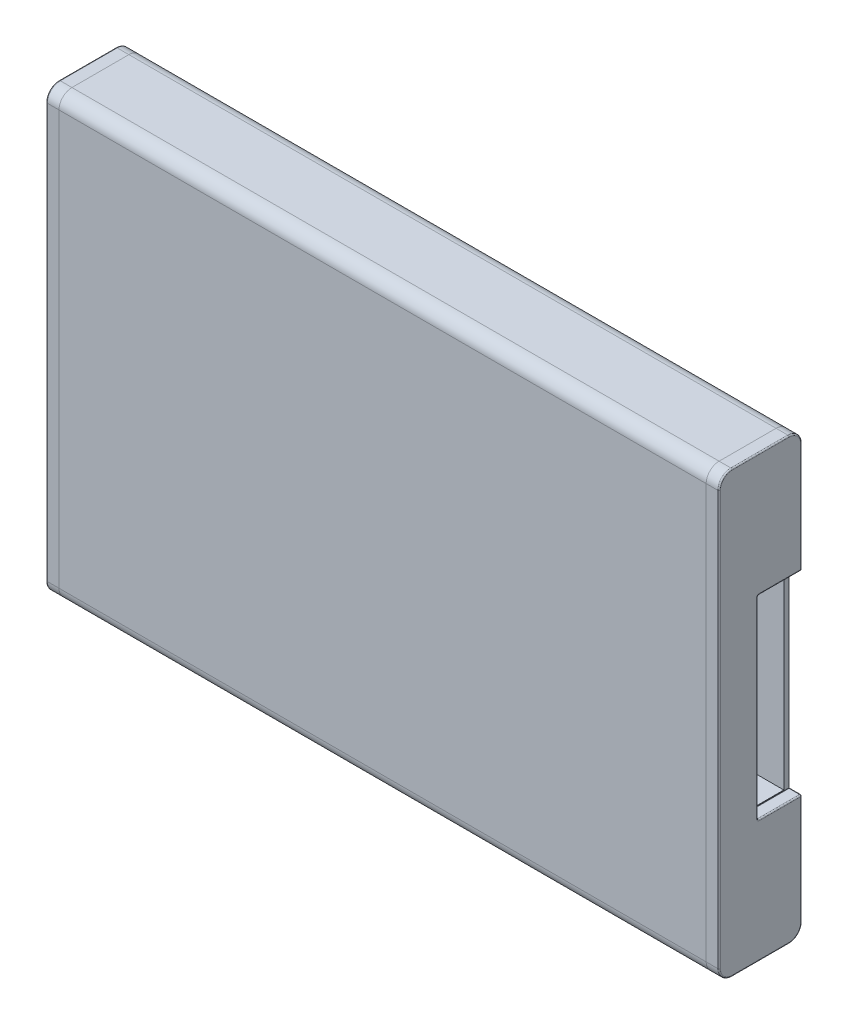
SolidWorks part; units mm, degrees
material "6061 Alloy"
ref_plane "Front Plane" through (0, 0, 0) normal (0, 0, 1) x (1, 0, 0)
ref_plane "Top Plane" through (0, 0, 0) normal (0, 1, 0) x (1, 0, 0)
ref_plane "Right Plane" through (0, 0, 0) normal (1, 0, 0) x (0, 0, -1)
sketch "Sketch1" plane through (0, 0, 0) normal (0, 0, 1) x (1, 0, 0)
  line L1 (0, 0) -> (255, 0)
  line L2 (0, 0) -> (0, 170)
  line L3 (0, 170) -> (255, 170)
  line L4 (255, 0) -> (255, 170)
  dimension "D1" = 255
  dimension "D2" = 170
extrude "Boss-Extrude1" add sketch "Sketch1" along normal blind 32
fillet "Fillet1" radius 5 4 edges at (127.5, 0, 32) (127.5, 0, 0) (127.5, 170, 32) (127.5, 170, 0)
sketch "Sketch2" plane through (255, 0, 0) normal (1, 0, 0) x (0, 0, -1)
  line L4 (-32, 165) -> (-32, 5)
  line L5 (-27, 0) -> (-5, 0)
  line L6 (0, 5) -> (0, 165)
  line L7 (-5, 170) -> (-27, 170)
  line L8 (-32, 165) -> (-32, 5)
  line L9 (-27, 0) -> (-5, 0)
  line L10 (0, 5) -> (0, 165)
  line L11 (-5, 170) -> (-27, 170)
  arc A4 (-32, 5) -> (-27, 0) centre (-27, 5) ccw
  arc A5 (-5, 0) -> (0, 5) centre (-5, 5) ccw
  arc A6 (0, 165) -> (-5, 170) centre (-5, 165) ccw
  arc A7 (-27, 170) -> (-32, 165) centre (-27, 165) ccw
  arc A8 (-32, 5) -> (-27, 0) centre (-27, 5) ccw
  arc A9 (-5, 0) -> (0, 5) centre (-5, 5) ccw
  arc A10 (0, 165) -> (-5, 170) centre (-5, 165) ccw
  arc A11 (-27, 170) -> (-32, 165) centre (-27, 165) ccw
  dimension "D1" = 0
extrude "Cut-Extrude1" cut sketch "Sketch2" against normal blind 5
sketch "Sketch3" plane through (250, 0, 0) normal (1, 0, 0) x (0, 0, -1)
  line L4 (-32, 165) -> (-32, 5)
  line L5 (-27, 0) -> (-5, 0)
  line L6 (0, 5) -> (0, 165)
  line L7 (-5, 170) -> (-27, 170)
  line L8 (-32, 165) -> (-32, 5)
  line L9 (-27, 0) -> (-5, 0)
  line L10 (0, 5) -> (0, 165)
  line L11 (-5, 170) -> (-27, 170)
  arc A4 (-27, 170) -> (-32, 165) centre (-27, 165) ccw
  arc A5 (-32, 5) -> (-27, 0) centre (-27, 5) ccw
  arc A6 (-5, 0) -> (0, 5) centre (-5, 5) ccw
  arc A7 (0, 165) -> (-5, 170) centre (-5, 165) ccw
  arc A8 (-27, 170) -> (-32, 165) centre (-27, 165) ccw
  arc A9 (-32, 5) -> (-27, 0) centre (-27, 5) ccw
  arc A10 (-5, 0) -> (0, 5) centre (-5, 5) ccw
  arc A11 (0, 165) -> (-5, 170) centre (-5, 165) ccw
  dimension "D1" = 0
extrude "Boss-Extrude2" add sketch "Sketch3" along normal blind 5 separate body
sketch "Sketch4" plane through (255, 0, 0) normal (1, 0, 0) x (0, 0, -1)
  line L0 (0, 5) -> (0, 165) construction
  line L1 (0, 122.5) -> (-17, 122.5)
  line L2 (0, 122.5) -> (0, 47.5)
  line L3 (0, 47.5) -> (-17, 47.5)
  line L4 (-17, 122.5) -> (-17, 47.5)
  line L5 (-32, 85) -> (0, 85) construction
  line L6 (-32, 165) -> (-32, 5) construction
  dimension "D1" = 75
  dimension "D2" = 17
  dimension "D3" = 37.5
extrude "Cut-Extrude2" cut sketch "Sketch4" against normal blind 5
sketch "Sketch5" plane through (250, 0, 0) normal (1, 0, 0) x (0, 0, -1)
  line L0 (0, 122.5) -> (-17, 122.5) construction
  line L1 (-2, 122.5) -> (-17, 122.5)
  line L2 (-2, 122.5) -> (-2, 47.5)
  line L3 (-2, 47.5) -> (-17, 47.5)
  line L4 (-17, 122.5) -> (-17, 47.5)
  line L5 (0, 5) -> (0, 165) construction
  dimension "D1" = 2
extrude "Cut-Extrude3" cut sketch "Sketch5" against normal blind 100
fillet "Fillet2" radius 0.5 19 edges at (250, 85, 17) (255, 85, 17) (255, 26.25, 0) (255, 1.4645, 1.4645) (255, 0, 16) (255, 1.4645, 30.5355) (255, 85, 32) (255, 168.5355, 30.5355) (255, 170, 16) (255, 168.5355, 1.4645) (252.5, 47.5, 17) (250, 47.5, 8.5) (252.5, 47.5, 0) (255, 47.5, 8.5) (252.5, 122.5, 0) (250, 122.5, 8.5) (252.5, 122.5, 17) (255, 122.5, 8.5) (255, 143.75, 0)
sketch "Sketch6" plane through (0, 0, 0) normal (-1, 0, 0) x (0, 0, 1)
  line L4 (5, 0) -> (27, 0)
  line L5 (32, 5) -> (32, 165)
  line L6 (27, 170) -> (5, 170)
  line L7 (0, 165) -> (0, 5)
  line L8 (5, 0) -> (27, 0)
  line L9 (32, 5) -> (32, 165)
  line L10 (27, 170) -> (5, 170)
  line L11 (0, 165) -> (0, 5)
  arc A4 (27, 0) -> (32, 5) centre (27, 5) ccw
  arc A5 (32, 165) -> (27, 170) centre (27, 165) ccw
  arc A6 (5, 170) -> (0, 165) centre (5, 165) ccw
  arc A7 (0, 5) -> (5, 0) centre (5, 5) ccw
  arc A8 (27, 0) -> (32, 5) centre (27, 5) ccw
  arc A9 (32, 165) -> (27, 170) centre (27, 165) ccw
  arc A10 (5, 170) -> (0, 165) centre (5, 165) ccw
  arc A11 (0, 5) -> (5, 0) centre (5, 5) ccw
  dimension "D1" = 0
extrude "Boss-Extrude3" add sketch "Sketch6" along normal blind 5 separate body
fillet "Fillet3" radius 0.5 8 edges at (-5, 168.5355, 1.4645) (-5, 170, 16) (-5, 168.5355, 30.5355) (-5, 85, 32) (-5, 1.4645, 30.5355) (-5, 0, 16) (-5, 1.4645, 1.4645) (-5, 85, 0)
